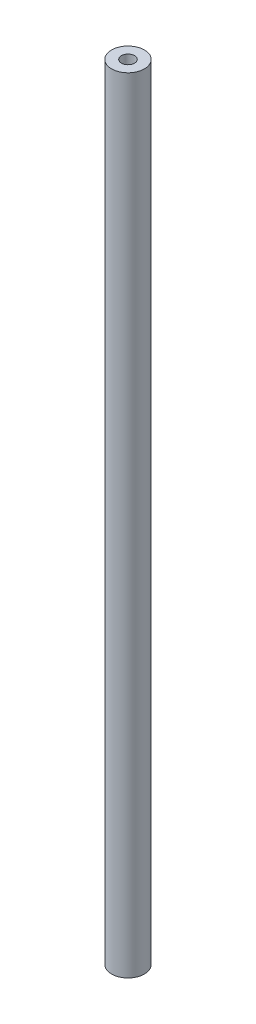
SolidWorks part; units mm, degrees
ref_plane "정면" through (0, 0, 0) normal (0, 0, 1) x (1, 0, 0)
ref_plane "윗면" through (0, 0, 0) normal (0, 1, 0) x (1, 0, 0)
ref_plane "우측면" through (0, 0, 0) normal (1, 0, 0) x (0, 0, -1)
sketch "스케치1" plane through (0, 0, 0) normal (0, 1, 0) x (1, 0, 0)
  circle A0 centre (0, 0) radius 5
extrude "보스-돌출1" add sketch "스케치1" along normal blind 238.84
sketch "스케치2" plane through (0, 238.84, 0) normal (0, 1, 0) x (1, 0, 0)
  circle A0 centre (0, 0) radius 2
extrude "컷-돌출1" cut sketch "스케치2" against normal blind 10
sketch "스케치3" plane through (0, 0, 0) normal (0, -1, 0) x (1, 0, 0)
  circle A0 centre (0, 0) radius 2
extrude "컷-돌출2" cut sketch "스케치3" against normal blind 10
